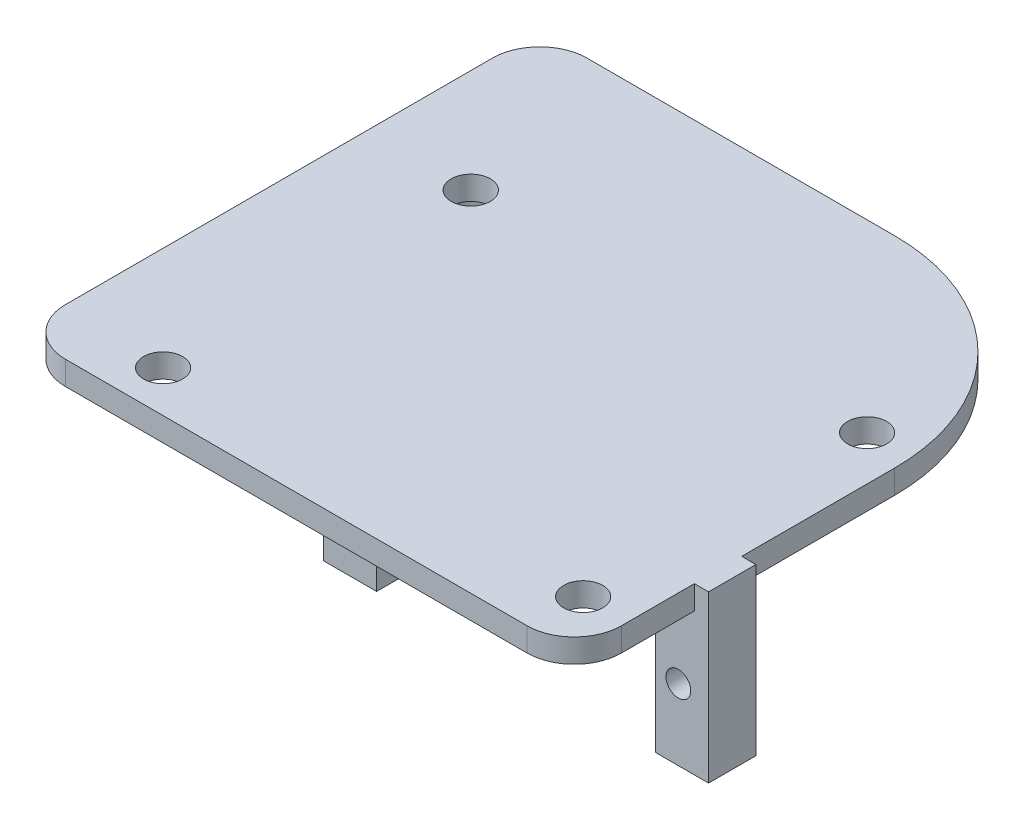
SolidWorks part; units mm, degrees
ref_plane "Front Plane" through (0, 0, 0) normal (0, 0, 1) x (1, 0, 0)
ref_plane "Top Plane" through (0, 0, 0) normal (0, 1, 0) x (1, 0, 0)
ref_plane "Right Plane" through (0, 0, 0) normal (1, 0, 0) x (0, 0, -1)
sketch "Sketch1" plane through (0, 0, 0) normal (0, 1, 0) x (1, 0, 0)
  line L1 (0, 0) -> (42, 0)
  line L2 (0, 0) -> (0, 33)
  line L3 (0, 33) -> (42, 33)
  line L4 (42, 0) -> (42, 33)
  dimension "D1" = 33
  dimension "D2" = 42
extrude "Boss-Extrude1" add sketch "Sketch1" along normal blind 2
fillet "Fillet1" radius 4 4 edges at (42, 1, -33) (42, 1, 0) (0, 1, -33) (0, 1, 0)
sketch "Sketch3" plane through (0, 0, 0) normal (0, -1, 0) x (1, 0, 0)
  circle A0 centre (3.75, -3.5) radius 1.65 construction
  circle A1 centre (3.75, -29.5) radius 1.65 construction
  circle A2 centre (38.25, -28.5) radius 1.65 construction
  circle A3 centre (38.25, -4.5) radius 1.65 construction
  circle A4 centre (3.75, -3.5) radius 1.65
  circle A5 centre (3.75, -29.5) radius 1.65
  circle A6 centre (38.25, -28.5) radius 1.65
  circle A7 centre (38.25, -4.5) radius 1.65
extrude "Cut-Extrude1" cut sketch "Sketch3" against normal blind 2
sketch "Sketch4" plane through (0, 0, 0) normal (0, -1, 0) x (1, 0, 0)
  line L0 (38, -33) -> (4, -33) construction
  line L1 (6.3629, -33) -> (0, -33)
  line L2 (6.3629, -33) -> (6.3629, -25.6491)
  line L3 (6.3629, -25.6491) -> (0, -25.6491)
  line L4 (0, -33) -> (0, -25.6491)
  line L5 (0, -29) -> (0, -4) construction
  line L6 (4, 0) -> (38, 0) construction
  line L7 (36.2973, 0) -> (42, 0)
  line L8 (36.2973, 0) -> (36.2973, -4.9581)
  line L9 (36.2973, -4.9581) -> (42, -4.9581)
  line L10 (42, 0) -> (42, -4.9581)
  line L11 (42, -4) -> (42, -29) construction
  line L12 (0, -16.5) -> (42, -16.5)
  line L13 (0, -33) -> (42, -33)
  line L14 (0, -33) -> (0, 0)
  line L15 (0, 0) -> (42, 0)
  line L16 (42, -33) -> (42, 0)
  line L17 (21, -33) -> (21, 0)
  circle A0 centre (21, -16.5) radius 2.5
  dimension "D1" = 5
sketch "Sketch5" plane through (0, 0, 0) normal (0, -1, 0) x (1, 0, 0)
  line L0 (42, -33) -> (42, 0) construction
  line L1 (42, -28.0798) -> (0, -28.0798)
  line L2 (42, -28.0798) -> (42, -44.0798)
  line L3 (42, -44.0798) -> (0, -44.0798)
  line L4 (0, -28.0798) -> (0, -44.0798)
  line L5 (0, -33) -> (42, -33) construction
  dimension "D1" = 16
  dimension "D2" = 4.9202
extrude "Boss-Extrude3" add sketch "Sketch5" against normal blind 2
sketch "Sketch6" plane through (0, 0, 0) normal (0, -1, 0) x (1, 0, 0)
  circle A0 centre (38.25, -28.5) radius 1.65
  circle A1 centre (3.7477, -29.5061) radius 1.6565
extrude "Cut-Extrude2" cut sketch "Sketch6" against normal blind 2
fillet "Fillet2" radius 17 1 edges at (42, 1, -44.0798)
fillet "Fillet3" radius 4 1 edges at (0, 1, -44.0798)
sketch "Sketch7" plane through (0, 0, 0) normal (0, -1, 0) x (1, 0, 0)
  line L0 (0, -40.0798) -> (0, -4) construction
  line L1 (4, 0) -> (-5, 0)
  line L2 (4, 0) -> (4, -44.0798)
  line L3 (4, -44.0798) -> (-5, -44.0798)
  line L4 (-5, 0) -> (-5, -44.0798)
  dimension "D1" = 4
  dimension "D2" = 5
extrude "Boss-Extrude4" add sketch "Sketch7" against normal blind 2
sketch "Sketch8" plane through (0, 0, 0) normal (0, -1, 0) x (1, 0, 0)
  circle A0 centre (3.75, -3.5) radius 1.65
  circle A1 centre (5.4084, -29.3711) radius 0.0097
  circle A2 centre (3.7477, -29.5061) radius 1.6565
  arc M1 (4, -27.8689) -> (4, -31.1432) centre (3.7477, -29.5061) cw
  line M2 (4, -31.1432) -> (4, -27.8689)
  arc M3 (4, -1.869) -> (4, -5.131) centre (3.75, -3.5) cw
  line M4 (4, -5.131) -> (4, -1.869)
extrude "Cut-Extrude3" cut sketch "Sketch8" against normal blind 2 contours A0 M4 | M3 M4 | M1 M2 | A2 M2
fillet "Fillet4" radius 4 2 edges at (-5, 1, -44.0798) (-5, 1, 0)
sketch "Sketch9" plane through (0, 0, 0) normal (0, -1, 0) x (1, 0, 0)
  line L0 (20, -28.5) -> (1.17, -28.5) construction
  line L1 (1.17, -28.5) -> (1.17, -43.75) construction
  line L2 (1.17, -43.75) -> (20, -43.75) construction
  line L3 (20, -43.75) -> (20, -38.625) construction
  line L4 (20, -28.5) -> (1.17, -28.5)
  line L5 (1.17, -28.5) -> (1.17, -43.75)
  line L6 (1.17, -43.75) -> (20, -43.75)
  line L7 (20, -43.75) -> (20, -38.625)
  line L8 (20, -43.75) -> (20, -28.5) construction
  line L9 (20, -43.75) -> (20, -28.5)
  circle A0 centre (3.7477, -29.5061) radius 1.6565 construction
  circle A1 centre (18, -41.75) radius 1 construction
  circle A2 centre (18, -30.5) radius 1 construction
  circle A3 centre (3.7477, -29.5061) radius 1.6565
  circle A4 centre (18, -41.75) radius 1
  circle A5 centre (18, -30.5) radius 1
  circle A6 centre (3.7477, -29.5061) radius 3
  circle M11 centre (3.7477, -29.5061) radius 1.6565
  dimension "D1" = 6
extrude "Boss-Extrude5" add sketch "Sketch9" along normal blind 10 contours L7 L9 L4 L5 L6 A5 A4 M11
sketch "Sketch10" plane through (0, 2, 0) normal (0, 1, 0) x (1, 0, 0)
  line L0 (42, 4) -> (42, 27.0798) construction
  line L1 (42, 12.15) -> (43.2, 12.15)
  line L2 (42, 12.15) -> (42, 14.15)
  line L3 (42, 14.15) -> (43.2, 14.15)
  line L4 (43.2, 12.15) -> (43.2, 14.15)
  line L6 (-1, 0) -> (38, 0) construction
  dimension "D1" = 1.2
  dimension "D2" = 12.15
  dimension "D3" = 2
extrude "Boss-Extrude6" add sketch "Sketch10" against normal up to surface (2 mm away) up to face at (18, 0, -42.75)
sketch "Sketch11" plane through (0, 0, 0) normal (0, -1, 0) x (1, 0, 0)
  line L0 (15.3949, -11.9) -> (15.3949, -7.15) construction
  line L1 (43.2, -12.15) -> (38.7, -12.15)
  line L2 (43.2, -12.15) -> (43.2, -14.15)
  line L3 (43.2, -14.15) -> (38.7, -14.15)
  line L4 (38.7, -12.15) -> (38.7, -14.15)
  line L5 (10.6449, -12.15) -> (15.1449, -12.15)
  line L6 (10.6449, -12.15) -> (10.6449, -14.15)
  line L7 (10.6449, -14.15) -> (15.1449, -14.15)
  line L8 (15.1449, -12.15) -> (15.1449, -14.15)
  dimension "D1" = 4.5
  dimension "D2" = 0
  dimension "D3" = 4.5
  dimension "D4" = 2
  dimension "D5" = 0.25
extrude "Boss-Extrude7" add sketch "Sketch11" along normal up to surface (12 mm away)
sketch "Sketch12" plane through (0, 0, -12.15) normal (0, 0, 1) x (1, 0, 0)
  arc A0 (12.2216, -6.5) -> (12.2216, -5.5) centre (13.1449, -6) ccw construction
  arc A1 (41.5682, -5.5) -> (41.5682, -6.5) centre (40.6449, -6) ccw construction
  arc A2 (12.2216, -6.5) -> (12.2216, -5.5) centre (13.1449, -6) ccw
  arc A3 (41.5682, -5.5) -> (41.5682, -6.5) centre (40.6449, -6) ccw
  circle A4 centre (40.6449, -6) radius 1.05
  circle A5 centre (13.1449, -6) radius 1.05
extrude "Cut-Extrude4" cut sketch "Sketch12" against normal blind 10 contours A3 A4 | A2 A5
sketch "Sketch13" plane through (20, 0, 0) normal (1, 0, 0) x (0, 0, -1)
  line L0 (28.5, -10) -> (28.5, 0) construction
  line L1 (28.5, -8.5) -> (30.5, -8.5)
  line L2 (28.5, -8.5) -> (28.5, -3.75)
  line L3 (28.5, -3.75) -> (30.5, -3.75)
  line L4 (30.5, -8.5) -> (30.5, -3.75)
  line L5 (43.75, -10) -> (28.5, -10) construction
  dimension "D1" = 1.5
  dimension "D2" = 4.75
  dimension "D3" = 2
extrude "Cut-Extrude5" cut sketch "Sketch13" against normal blind 2
sketch "Sketch15" plane through (0, 0, -12.15) normal (0, 0, 1) x (1, 0, 0)
  line L0 (10.6449, 0) -> (10.6449, -12) construction
  line L1 (10.6449, -12) -> (15.1449, -12) construction
  line L2 (15.1449, -12) -> (15.1449, 0) construction
  line L3 (15.1449, 0) -> (10.6449, 0) construction
  line L4 (42, 2) -> (42, 0) construction
  line L5 (42, 0) -> (38.7, 0) construction
  line L6 (38.7, 0) -> (38.7, -12) construction
  line L7 (38.7, -12) -> (43.2, -12) construction
  line L8 (43.2, -12) -> (43.2, 2) construction
  line L9 (43.2, 2) -> (42, 2) construction
  line L10 (10.6449, 0) -> (10.6449, -12)
  line L11 (10.6449, -12) -> (15.1449, -12)
  line L12 (15.1449, -12) -> (15.1449, 0)
  line L13 (15.1449, 0) -> (10.6449, 0)
  line L14 (42, 2) -> (42, 0)
  line L15 (42, 0) -> (38.7, 0)
  line L16 (38.7, 0) -> (38.7, -12)
  line L17 (38.7, -12) -> (43.2, -12)
  line L18 (43.2, -12) -> (43.2, 2)
  line L19 (43.2, 2) -> (42, 2)
  circle A0 centre (13.1449, -6) radius 1.05 construction
  circle A1 centre (40.6449, -6) radius 1.05 construction
  circle A2 centre (13.1449, -6) radius 1.05
  circle A3 centre (40.6449, -6) radius 1.05
extrude "Boss-Extrude8" add sketch "Sketch15" along normal blind 2
